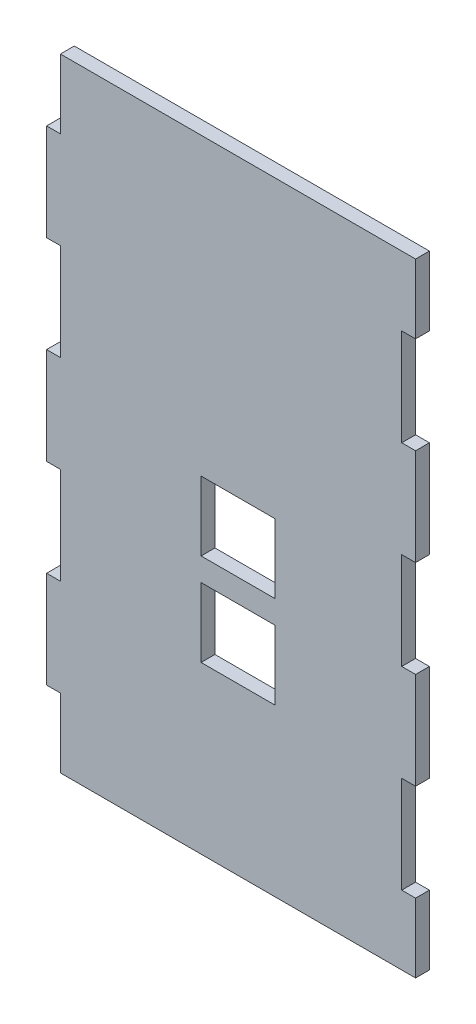
SolidWorks part; units mm, degrees
ref_plane "Plano frontal" through (0, 0, 0) normal (0, 0, 1) x (1, 0, 0)
ref_plane "Plano superior" through (0, 0, 0) normal (0, 1, 0) x (1, 0, 0)
ref_plane "Plano direito" through (0, 0, 0) normal (1, 0, 0) x (0, 0, -1)
sketch "Esboço1" plane through (0, 0, 0) normal (0, 0, 1) x (1, 0, 0)
  line L1 (38.5, -67.5) -> (-38.5, -67.5)
  line L2 (38.5, -67.5) -> (38.5, 67.5)
  line L3 (38.5, 67.5) -> (-38.5, 67.5)
  line L4 (-38.5, -67.5) -> (-38.5, 67.5)
  line L5 (38.5, -67.5) -> (-38.5, 67.5) construction
  line L6 (38.5, 67.5) -> (-38.5, -67.5) construction
  point P0 (0, 0)
  dimension "D1" = 77
  dimension "D2" = 135
extrude "Ressalto-extrusão1" add sketch "Esboço1" along normal blind 3
sketch "Esboço4" plane through (0, 0, 3) normal (0, 0, 1) x (1, 0, 0)
  line L0 (38.5, -67.5) -> (38.5, 67.5) construction
  line L1 (38.5, 52.5) -> (35.5, 52.5)
  line L2 (38.5, 52.5) -> (38.5, 31.5)
  line L3 (38.5, 31.5) -> (35.5, 31.5)
  line L4 (35.5, 52.5) -> (35.5, 31.5)
  line L5 (38.5, 67.5) -> (-38.5, 67.5) construction
  line L6 (35.5, 10.5) -> (35.5, -10.5)
  line L7 (38.5, 10.5) -> (38.5, -10.5)
  line L8 (38.5, 10.5) -> (35.5, 10.5)
  line L9 (38.5, -10.5) -> (35.5, -10.5)
  line L10 (35.5, -31.5) -> (35.5, -52.5)
  line L11 (38.5, -31.5) -> (38.5, -52.5)
  line L12 (38.5, -31.5) -> (35.5, -31.5)
  line L13 (38.5, -52.5) -> (35.5, -52.5)
  dimension "D1" = 3
  dimension "D2" = 21
  dimension "D3" = 15
  dimension "D5" = 21
  dimension "D4" = 3
extrude "Corte-extrusão1" cut sketch "Esboço4" against normal through all
sketch "Esboço5" plane through (0, 0, 3) normal (0, 0, 1) x (1, 0, 0)
  line L0 (-38.5, 67.5) -> (-38.5, -67.5) construction
  line L1 (-38.5, 52.5) -> (-41.5, 52.5)
  line L2 (-38.5, 52.5) -> (-38.5, 31.5)
  line L3 (-38.5, 31.5) -> (-41.5, 31.5)
  line L4 (-41.5, 52.5) -> (-41.5, 31.5)
  line L7 (35.5, 31.5) -> (38.5, 31.5) construction
  line L8 (38.5, 52.5) -> (35.5, 52.5) construction
  dimension "D1" = 3
extrude "Ressalto-extrusão2" add sketch "Esboço5" against normal blind 3
pattern_linear "Padrão linear1" count 3 spacing 42 along (0, -1, 0) of "Ressalto-extrusão2"
sketch "Esboço6" plane through (0, 0, 3) normal (0, 0, 1) x (1, 0, 0)
  line L0 (-38.5, -67.5) -> (38.5, -67.5) construction
  line L1 (-8, -16.5) -> (8, -16.5)
  line L2 (-8, -16.5) -> (-8, -31.5)
  line L3 (-8, -31.5) -> (8, -31.5)
  line L4 (8, -16.5) -> (8, -31.5)
  point P6 (0, -16.5)
  dimension "D1" = 36
  dimension "D2" = 16
  dimension "D3" = 15
extrude "Corte-extrusão2" cut sketch "Esboço6" against normal through all contours L1 L4 L3 L2
pattern_linear "Padrão linear2" count 2 spacing 20 along (0, 1, 0) of "Corte-extrusão2"
